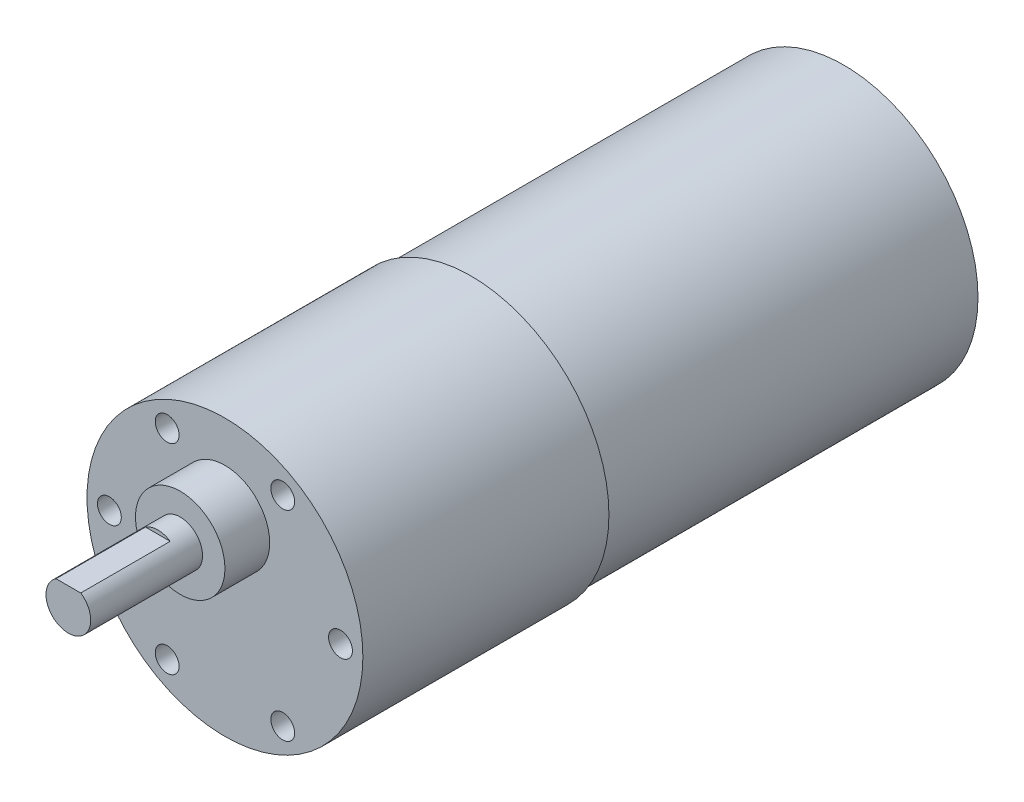
SolidWorks part; units mm, degrees
ref_plane "前视基准面" through (0, 0, 0) normal (0, 0, 1) x (1, 0, 0)
ref_plane "上视基准面" through (0, 0, 0) normal (0, 1, 0) x (1, 0, 0)
ref_plane "右视基准面" through (0, 0, 0) normal (1, 0, 0) x (0, 0, -1)
sketch "草图1" plane through (0, 0, 0) normal (0, 0, 1) x (1, 0, 0)
  circle A0 centre (0, 0) radius 18.5
extrude "凸台-拉伸1" add sketch "草图1" along normal blind 33
sketch "草图2" plane through (0, 0, 0) normal (0, 0, -1) x (-1, 0, 0)
  circle A0 centre (0, 0) radius 18
extrude "凸台-拉伸2" add sketch "草图2" along normal blind 50
sketch "草图3" plane through (0, 0, 33) normal (0, 0, 1) x (1, 0, 0)
  line L0 (-32.7351, 0) -> (29.8152, 0) construction
  circle A0 centre (0, 0) radius 15.5 construction
  circle A1 centre (-15.5, 0) radius 1.6
  circle A2 centre (-7.75, 13.4234) radius 1.6
  circle A3 centre (7.75, 13.4234) radius 1.6
  circle A4 centre (15.5, 0) radius 1.6
  circle A5 centre (7.75, -13.4234) radius 1.6
  circle A6 centre (-7.75, -13.4234) radius 1.6
  point P19 (0, 0)
  dimension "D1" = 6
  dimension "D2" = 3.2
extrude "切除-拉伸1" cut sketch "草图3" against normal blind 6
sketch "草图4" plane through (0, 0, 33) normal (0, 0, 1) x (1, 0, 0)
  circle A0 centre (0, 7) radius 6
  dimension "D2" = 12
  dimension "D1" = 7
extrude "凸台-拉伸3" add sketch "草图4" along normal blind 6
sketch "草图5" plane through (0, 0, 39) normal (0, 0, 1) x (1, 0, 0)
  circle A0 centre (0, 7) radius 3
extrude "凸台-拉伸4" add sketch "草图5" along normal blind 15
sketch "草图6" plane through (0, 0, 54) normal (0, 0, 1) x (1, 0, 0)
  line L0 (-1.6583, 9.5) -> (1.6583, 9.5)
  arc A0 (1.6583, 9.5) -> (-1.6583, 9.5) centre (0, 7) ccw
  dimension "D2" = 6
  dimension "D1" = 2.5
extrude "切除-拉伸2" cut sketch "草图6" against normal blind 12
